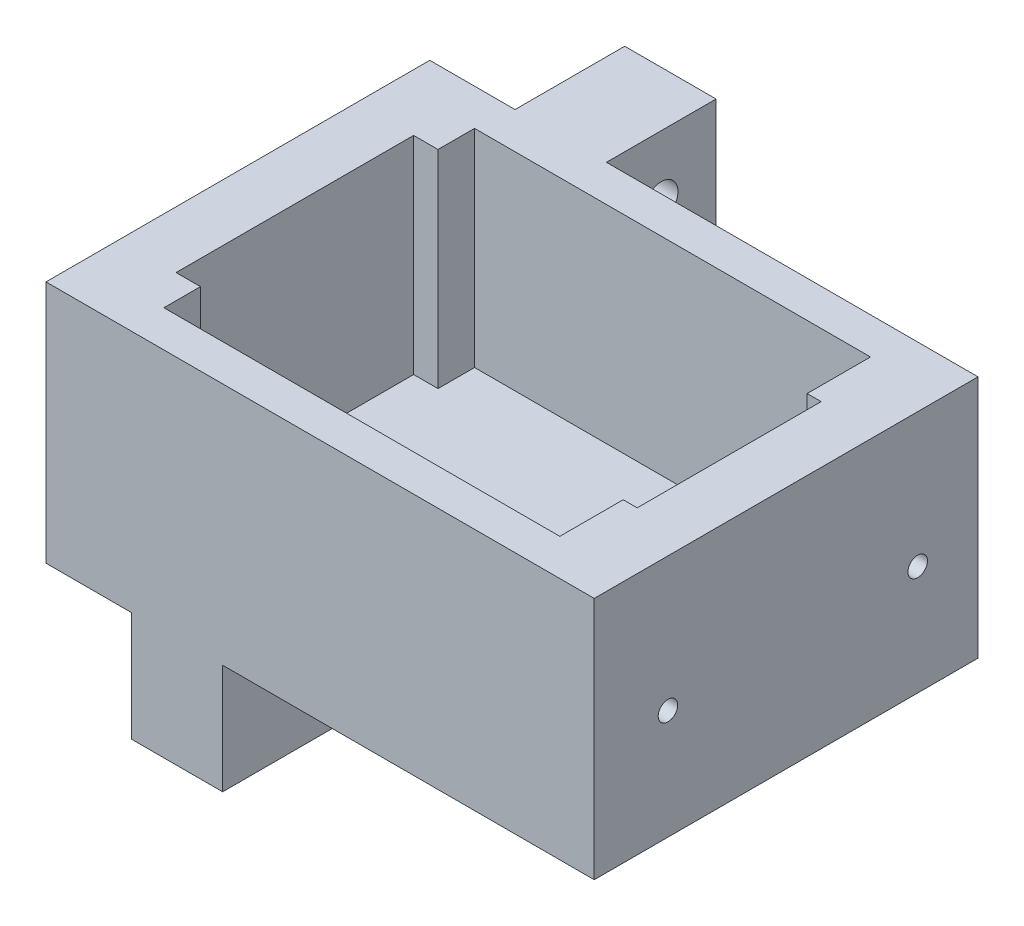
SolidWorks part; units mm, degrees
ref_plane "Front Plane" through (0, 0, 0) normal (0, 0, 1) x (1, 0, 0)
ref_plane "Top Plane" through (0, 0, 0) normal (0, 1, 0) x (1, 0, 0)
ref_plane "Right Plane" through (0, 0, 0) normal (1, 0, 0) x (0, 0, -1)
sketch "Sketch1" plane through (0, 0, 0) normal (0, 1, 0) x (1, 0, 0)
  line L1 (0, 0) -> (45, 0)
  line L2 (0, 0) -> (0, 31.5)
  line L3 (0, 31.5) -> (45, 31.5)
  line L4 (45, 0) -> (45, 31.5)
  dimension "D1" = 31.5
  dimension "D2" = 45
extrude "Boss-Extrude1" add sketch "Sketch1" along normal blind 20
sketch "Sketch2" plane through (0, 20, 0) normal (0, 1, 0) x (1, 0, 0)
  line L0 (22.5, 34.3711) -> (22.5, -3.2198) construction
  line L1 (0, 31.5) -> (0, 0) construction
  line L2 (39.175, 28.5) -> (6.675, 28.5)
  line L3 (6.675, 28.5) -> (6.675, 25.5)
  line L4 (6.675, 25.5) -> (4.675, 25.5)
  line L5 (4.675, 25.5) -> (4.675, 6)
  line L6 (4.675, 6) -> (6.675, 6)
  line L7 (6.675, 6) -> (6.675, 3)
  line L8 (6.675, 3) -> (39.175, 3)
  line L9 (39.175, 3) -> (39.175, 8.2)
  line L10 (39.175, 8.2) -> (40.325, 8.2)
  line L11 (40.325, 8.2) -> (40.325, 23.3)
  line L12 (40.325, 23.3) -> (39.175, 23.3)
  line L13 (39.175, 23.3) -> (39.175, 28.5)
  line L14 (45, 0) -> (45, 31.5) construction
  line L15 (0, 0) -> (45, 0) construction
  line L16 (45, 31.5) -> (0, 31.5) construction
  dimension "D1" = 22.5
  dimension "D2" = 1.15
  dimension "D3" = 32.5
  dimension "D4" = 3
  dimension "D5" = 19.5
  dimension "D6" = 5.2
  dimension "D7" = 15.1
  dimension "D8" = 4.675
  dimension "D9" = 4.675
  dimension "D10" = 2
  dimension "D11" = 3
  dimension "D12" = 3
  dimension "D13" = 3
extrude "Cut-Extrude1" cut sketch "Sketch2" against normal blind 17
sketch "Sketch3" plane through (39.175, 0, 0) normal (-1, 0, 0) x (0, 0, 1)
  line L3 (-8.2, 3) -> (-8.2, 20) construction
  line L4 (-8.2, 3) -> (-23.3, 3) construction
  line L5 (-23.3, 3) -> (-23.3, 20) construction
  line L6 (-8.2, 3) -> (-8.2, 20)
  line L7 (-8.2, 3) -> (-23.3, 3)
  line L8 (-23.3, 3) -> (-23.3, 20)
  circle A2 centre (-26.55, 9) radius 0.8
  circle A3 centre (-6.05, 9) radius 0.8
  dimension "D5" = 1.6
  dimension "D6" = 6
  dimension "D7" = 20.5
  dimension "D8" = 3.25
extrude "Cut-Extrude2" cut sketch "Sketch3" against normal up to surface (5.825 mm away) contours A2 | A3 up to face at (45, 10, -15.75)
sketch "Sketch4" plane through (6.675, 0, 0) normal (1, 0, 0) x (0, 0, -1)
  line L3 (25.5, 3) -> (25.5, 20) construction
  line L4 (25.5, 3) -> (6, 3) construction
  line L5 (6, 3) -> (6, 20) construction
  line L6 (25.5, 3) -> (25.5, 20)
  line L7 (25.5, 3) -> (6, 3)
  line L8 (6, 3) -> (6, 20)
  circle A2 centre (5, 5.4) radius 0.8
  circle A3 centre (25.5, 5.4) radius 0.8
  dimension "D5" = 1.6
  dimension "D6" = 20.5
  dimension "D7" = 1
  dimension "D8" = 2.4
extrude "Cut-Extrude3" [suppressed] cut sketch "Sketch4" against normal up to surface (6.675 mm away) contours A3 | A2
sketch "Sketch5" plane through (0, 0, 0) normal (-1, 0, 0) x (0, 0, 1)
  line L0 (-31.5, 0) -> (0, 0)
  line L1 (-31.5, 0) -> (-31.5, -9)
  line L2 (0, 0) -> (0, -9)
  line L3 (-31.5, -9) -> (0, -9)
  line L4 (-31.5, -4.5) -> (0, -4.5) construction
  line L5 (-30.5, 0) -> (-30.5, -9)
  line L6 (-31.5, 0) -> (-31.5, 20)
  line L7 (-31.5, 0) -> (-40.5, 0)
  line L8 (-31.5, 20) -> (-40.5, 20)
  line L9 (-40.5, 0) -> (-40.5, 20)
  line L10 (-36, 20) -> (-36, 0) construction
  circle A0 centre (-24, -4.5) radius 1.375
  circle A1 centre (-7.5, -4.5) radius 1.375
  circle A2 centre (-36, 15) radius 1.375
  circle A3 centre (-36, 5) radius 1.375
  line M17 (-31.5, 20) -> (-31.5, 0)
  dimension "D2" = 2.75
  dimension "D7" = 2.75
  dimension "D1" = 9
  dimension "D3" = 1
  dimension "D4" = 7.5
  dimension "D5" = 7.5
  dimension "D6" = 9
  dimension "D8" = 5
  dimension "D9" = 5
extrude "Boss-Extrude2" add sketch "Sketch5" against normal blind 7.5 from offset 7 contours L0 L5 L3 L2 A1 A0 | L9 L7 L8 A3 A2 M17
